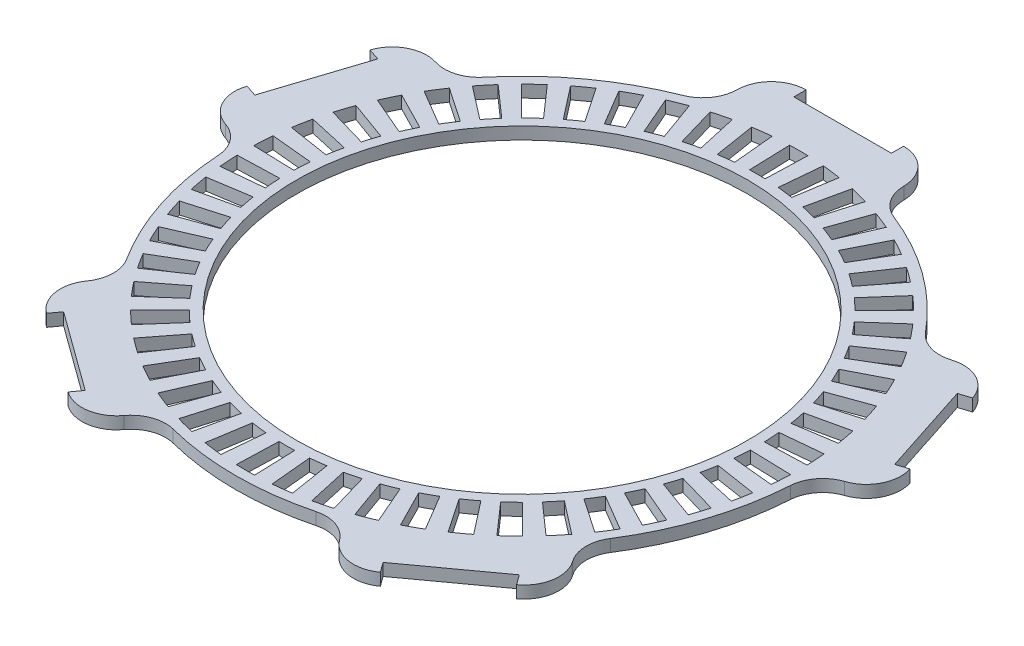
SolidWorks part; units mm, degrees
ref_plane "Front Plane" through (0, 0, 0) normal (0, 0, 1) x (1, 0, 0)
ref_plane "Top Plane" through (0, 0, 0) normal (0, 1, 0) x (1, 0, 0)
ref_plane "Right Plane" through (0, 0, 0) normal (1, 0, 0) x (0, 0, -1)
sketch "Sketch1" plane through (0, 0, 0) normal (0, 1, 0) x (1, 0, 0)
  circle A0 centre (0, 0) radius 23.5
  circle A1 centre (0, 0) radius 18.5
  dimension "D1" = 37
  dimension "D2" = 5
extrude "Boss-Extrude1" add sketch "Sketch1" along normal blind 1
sketch "Sketch2" plane through (0, 1, 0) normal (0, 1, 0) x (1, 0, 0)
  line L0 (-0.75, 22.6876) -> (-0.6377, 19.2895)
  line L1 (0.6377, 19.2895) -> (0.75, 22.6876)
  arc A0 (-0.75, 22.6876) -> (0.75, 22.6876) centre (0, 0) cw
  arc A1 (-0.6377, 19.2895) -> (0.6377, 19.2895) centre (0, 0) cw
  circle A2 centre (0, 0) radius 23.5 construction
  circle A3 centre (0, 0) radius 18.5 construction
  point P6 (0, 19.3)
  point P7 (0, 22.7)
  dimension "D2" = 0.8
  dimension "D3" = 0.8
  dimension "D1" = 1.5
extrude "Cut-Extrude1" cut sketch "Sketch2" against normal through all
pattern_circular "CirPattern1" count 50 over 360 about axis through (0, 0, 0) along (0, 1, 0) of "Cut-Extrude1"
sketch "Sketch3" plane through (0, 1, 0) normal (0, 1, 0) x (1, 0, 0)
  line L0 (0, 23.5) -> (0, 26.2866)
  line L1 (0, 26.2866) -> (4, 26.2866)
  line L2 (4, 26.2866) -> (4, 27.2866)
  arc A0 (4, 27.2866) -> (6.8415, 24.4711) centre (4, 24.4449) cw
  arc A1 (6.8415, 24.4711) -> (8.6384, 21.8547) centre (9.683, 24.4974) ccw
  circle A2 centre (0, 0) radius 23.5 construction
  arc A3 (8.6384, 21.8547) -> (0, 23.5) centre (0, 0) ccw
  dimension "D1" = 4
  dimension "D2" = 1
extrude "Boss-Extrude2" add sketch "Sketch3" against normal up to surface (1 mm away) up to face at (-2.6313, 0, -20.8287)
mirror "Mirror1" about plane through (0, 0, 0) normal (1, 0, 0) of "Boss-Extrude2"
pattern_circular "CirPattern2" count 5 over 360 about axis through (0, 0, 0) along (0, 1, 0) of "Mirror1", "Boss-Extrude2"
